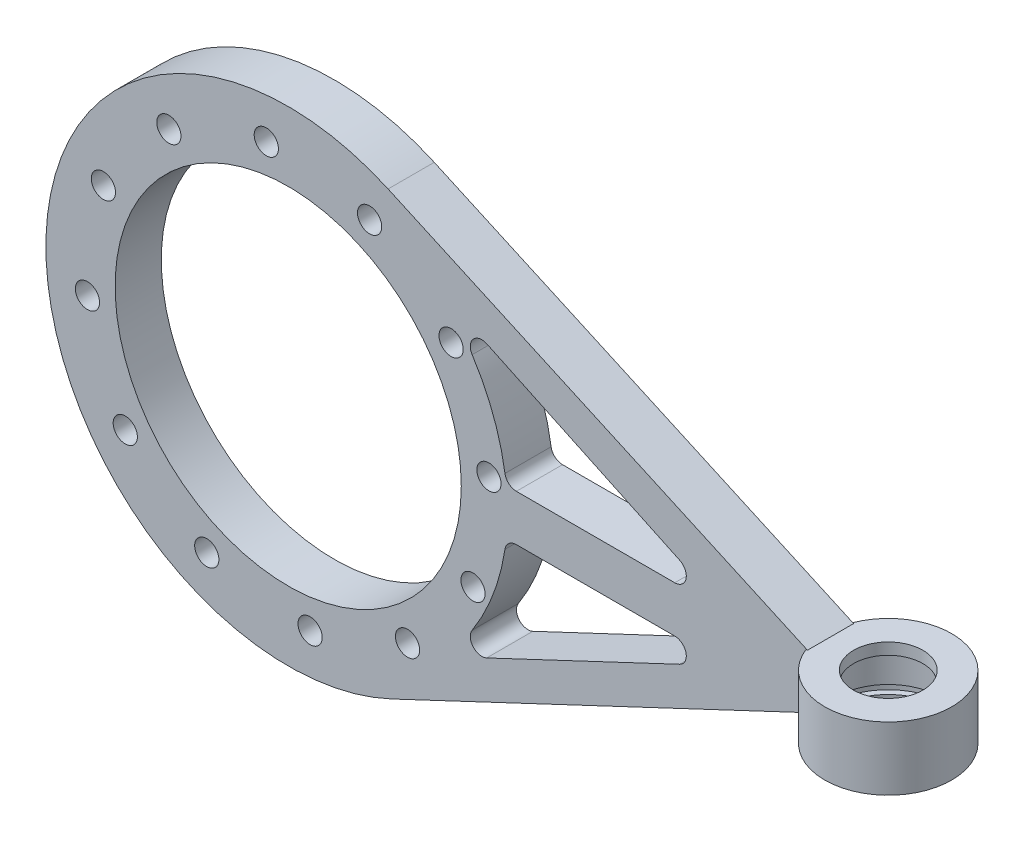
SolidWorks part; units mm, degrees
ref_plane "前视基准面" through (0, 0, 0) normal (0, 0, 1) x (1, 0, 0)
ref_plane "上视基准面" through (0, 0, 0) normal (0, 1, 0) x (1, 0, 0)
ref_plane "右视基准面" through (0, 0, 0) normal (1, 0, 0) x (0, 0, -1)
other "Configuration Table"
sketch "草图1" plane through (0, 0, 0) normal (0, 0, 1) x (1, 0, 0)
  circle A0 centre (0, 0) radius 42
  dimension "D1" = 84
extrude "凸台-拉伸1" add sketch "草图1" along normal blind 3
sketch "草图2" plane through (0, 0, 3) normal (0, 0, 1) x (1, 0, 0)
  line L0 (0, 0) -> (150.9371, 0) construction
  line L1 (100, 22.7173) -> (100, -21.6499) construction
  line L3 (89, 5.375) -> (100, 5.375)
  line L4 (89, 5.375) -> (89, -5.625)
  line L8 (89, -5.625) -> (100, -5.625)
  line L9 (100, 5.375) -> (100, -5.625)
  dimension "D2" = 11
  dimension "D1" = 100
  dimension "D3" = 5.375
  dimension "D4" = 11
revolve "旋转1" add sketch "草图2" angle 360 about L1
sketch "草图3" plane through (0, 0, 3) normal (0, 0, 1) x (1, 0, 0)
  line L0 (17.3147, 38.2649) -> (90, 5.375)
  line L1 (17.9116, -37.9891) -> (90, -4)
  line L4 (90, 5.375) -> (90, -4)
  circle A1 centre (0, 0) radius 42
  arc A2 (17.3147, 38.2649) -> (17.9116, -37.9891) centre (0, 0) ccw
  dimension "D2" = 90
  dimension "D3" = 5.375
  dimension "D4" = 4
  dimension "D1" = 0
extrude "凸台-拉伸2" add sketch "草图3" along normal mid plane 8
sketch "草图4" plane through (0, -5.625, 0) normal (0, -1, 0) x (1, 0, 0)
  circle A0 centre (100, 3) radius 6
  dimension "D1" = 12
extrude "切除-拉伸1" cut sketch "草图4" against normal blind 25
sketch "草图5" plane through (0, -5.625, 0) normal (0, -1, 0) x (1, 0, 0)
  circle A0 centre (100, 3) radius 9
  dimension "D1" = 18
extrude "切除-拉伸2" cut sketch "草图5" against normal offset from surface (9 mm away) 2 up to face at (100, 5.375, 9)
sketch "草图6" plane through (0, 3.375, 0) normal (0, -1, 0) x (1, 0, 0)
  circle A0 centre (100, 3) radius 10
  circle A1 centre (100, 3) radius 9 construction
  circle A2 centre (100, 3) radius 9 construction
  circle A3 centre (100, 3) radius 9
  circle M1 centre (100, 3) radius 9
  dimension "D1" = 1
extrude "切除-拉伸3" cut sketch "草图6" along normal blind 1.5 from offset 6.5 contours A0 M1 | A3
sketch "草图7" plane through (0, 0, 7) normal (0, 0, 1) x (1, 0, 0)
  line L0 (26.3566, -27.3739) -> (75.9309, -4)
  line L1 (0, 0) -> (55.8434, 0) construction
  line L2 (17.9116, -37.9891) -> (89.753, -4.1164) construction
  line L4 (37.7889, -4) -> (75.9309, -4)
  line L5 (37.7889, 4) -> (75.9309, 4)
  line L6 (26.3566, 27.3739) -> (75.9309, 4)
  circle A0 centre (0, 0) radius 30
  arc A1 (26.3566, -27.3739) -> (37.7889, -4) centre (0, 0) ccw
  arc A2 (26.3566, 27.3739) -> (37.7889, 4) centre (0, 0) cw
  dimension "D1" = 60
  dimension "D3" = 8
  dimension "D2" = 6
  dimension "D4" = 4
extrude "切除-拉伸4" cut sketch "草图7" against normal blind 30
fillet "圆角1" radius 2 6 edges at (37.7889, 4, 3) (26.3566, 27.3739, 3) (75.9309, 4, 3) (75.9309, -4, 3) (37.7889, -4, 3) (26.3566, -27.3739, 3)
sketch "草图8" plane through (0, 0, 7) normal (0, 0, 1) x (1, 0, 0)
  line L4 (89.753, 5.375) -> (90, 5.375)
  line L5 (90, 5.375) -> (17.3147, 38.2649)
  line L6 (17.9116, -37.9891) -> (89.753, -4.1164)
  line L7 (89.753, -4.1164) -> (89.753, 5.375)
  line L8 (89.753, 5.375) -> (90, 5.375)
  line L9 (90, 5.375) -> (17.3147, 38.2649)
  line L10 (17.9116, -37.9891) -> (89.753, -4.1164)
  line L11 (89.753, -4.1164) -> (89.753, 5.375)
  circle A0 centre (34.7937, 3.7944) radius 2.1 construction
  arc A1 (17.3147, 38.2649) -> (17.9116, -37.9891) centre (0, 0) ccw
  arc A2 (17.3147, 38.2649) -> (17.9116, -37.9891) centre (0, 0) ccw
  circle A3 centre (28.235, 20.6829) radius 2.1 construction
  circle A4 centre (14.1108, 32.0294) radius 2.1 construction
  circle A5 centre (-3.7944, 34.7937) radius 2.1 construction
  circle A6 centre (-20.6829, 28.235) radius 2.1 construction
  circle A7 centre (32.0294, -14.1108) radius 2.1 construction
  circle A8 centre (20.6829, -28.235) radius 2.1 construction
  circle A9 centre (3.7944, -34.7937) radius 2.1 construction
  circle A10 centre (-14.1108, -32.0294) radius 2.1 construction
  circle A11 centre (-28.235, -20.6829) radius 2.1 construction
  circle A12 centre (-34.7937, -3.7944) radius 2.1 construction
  circle A13 centre (-32.0294, 14.1108) radius 2.1 construction
  circle A14 centre (34.7937, 3.7944) radius 2.1
  circle A15 centre (28.235, 20.6829) radius 2.1
  circle A16 centre (14.1108, 32.0294) radius 2.1
  circle A17 centre (-3.7944, 34.7937) radius 2.1
  circle A18 centre (-20.6829, 28.235) radius 2.1
  circle A19 centre (32.0294, -14.1108) radius 2.1
  circle A20 centre (20.6829, -28.235) radius 2.1
  circle A21 centre (3.7944, -34.7937) radius 2.1
  circle A22 centre (-14.1108, -32.0294) radius 2.1
  circle A23 centre (-28.235, -20.6829) radius 2.1
  circle A24 centre (-34.7937, -3.7944) radius 2.1
  circle A25 centre (-32.0294, 14.1108) radius 2.1
  dimension "D1" = 0
extrude "切除-拉伸5" cut sketch "草图8" against normal through all contours A16 | A17 | A18 | A25 | A24 | A23 | A22 | A21 | A20 | A19 | A14 | A15
